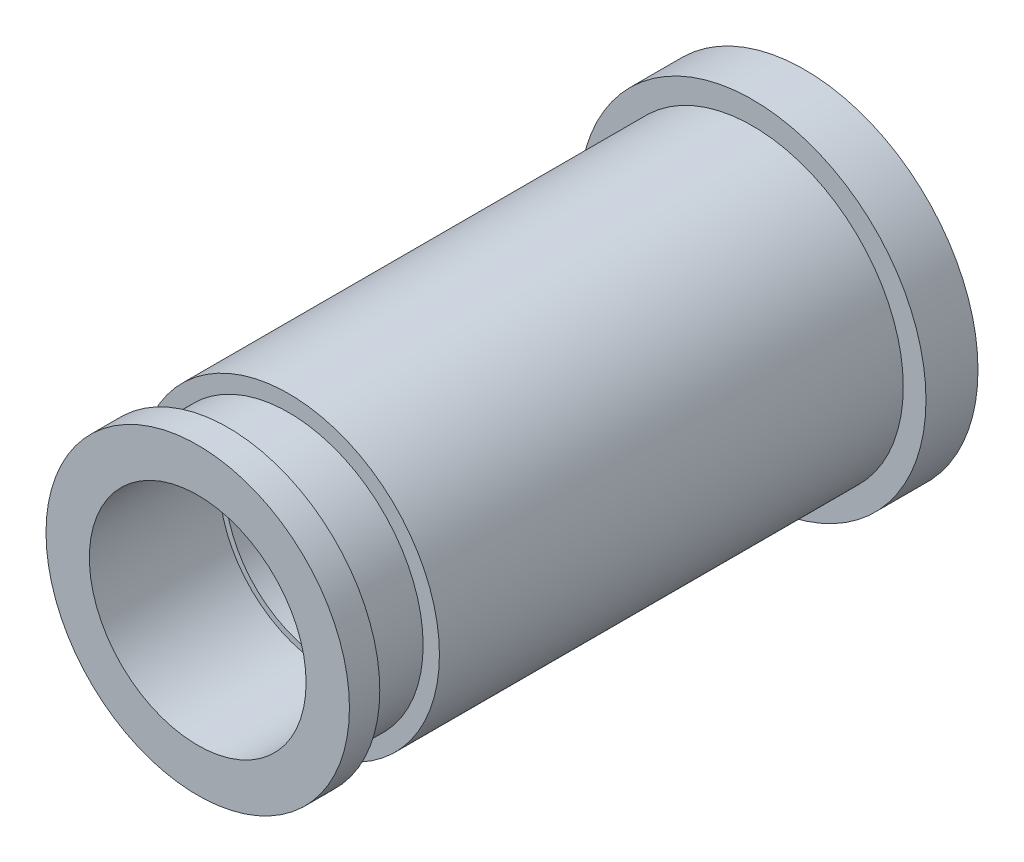
SolidWorks part; units mm, degrees
material "CI"
ref_plane "Front Plane" through (0, 0, 0) normal (0, 0, 1) x (1, 0, 0)
ref_plane "Top Plane" through (0, 0, 0) normal (0, 1, 0) x (1, 0, 0)
ref_plane "Right Plane" through (0, 0, 0) normal (1, 0, 0) x (0, 0, -1)
sketch "Sketch1" plane through (0, 0, 0) normal (1, 0, 0) x (0, 0, -1)
  line L0 (-20.5397, 0) -> (46244.6762, 0) construction
  line L1 (-61.2065, 19.8438) -> (-37.394, 19.8438)
  line L2 (-61.2065, 19.8438) -> (-61.2065, 27.7812)
  line L3 (-61.2065, 27.7812) -> (-55.6503, 27.7812)
  line L4 (-55.6503, 27.7812) -> (-55.6503, 24.6062)
  line L5 (-55.6503, 24.6062) -> (-44.5378, 24.6062)
  line L6 (-44.5378, 24.6062) -> (-44.5378, 27.5906)
  line L7 (-44.5378, 27.5906) -> (40.3935, 27.5906)
  line L8 (40.3935, 27.5906) -> (40.3935, 31.75)
  line L9 (40.3935, 31.75) -> (49.9185, 31.75)
  line L10 (49.9185, 31.75) -> (49.9185, 18.7946)
  line L11 (-37.394, 19.8438) -> (-37.394, 18.7946)
  line L12 (-37.394, 18.7946) -> (49.9185, 18.7946)
  dimension "D1" = 23.8125
  dimension "D2" = 55.5625
  dimension "D3" = 49.2125
  dimension "D4" = 5.5562
  dimension "D5" = 11.1125
  dimension "D6" = 39.6875
  dimension "D7" = 63.5
  dimension "D8" = 9.525
  dimension "D9" = 111.125
revolve "Revolve1" add sketch "Sketch1" angle 360 about L0
fillet "Fillet1" radius 0.7937 1 edges at (18.7946, 0, -49.9185)
